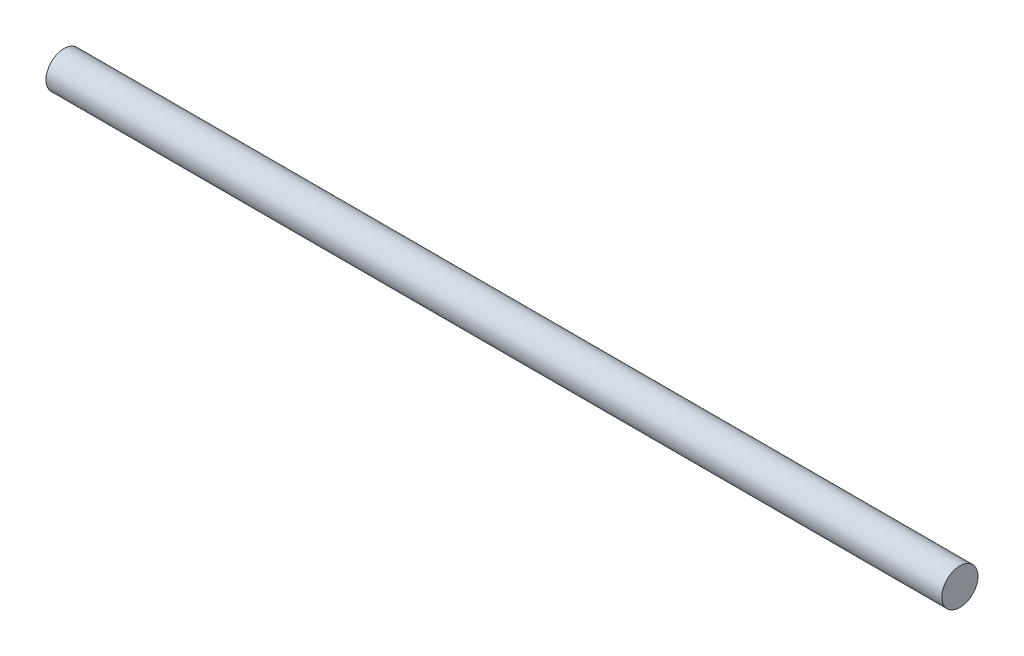
SolidWorks part; units mm, degrees
ref_plane "前视基准面" through (0, 0, 0) normal (0, 0, 1) x (1, 0, 0)
ref_plane "上视基准面" through (0, 0, 0) normal (0, 1, 0) x (1, 0, 0)
ref_plane "右视基准面" through (0, 0, 0) normal (1, 0, 0) x (0, 0, -1)
sketch "草图1" plane through (0, 0, 0) normal (1, 0, 0) x (0, 0, -1)
  circle A0 centre (0, 0) radius 2.625
  dimension "D1" = 5.25
extrude "凸台-拉伸1" add sketch "草图1" along normal mid plane 130
